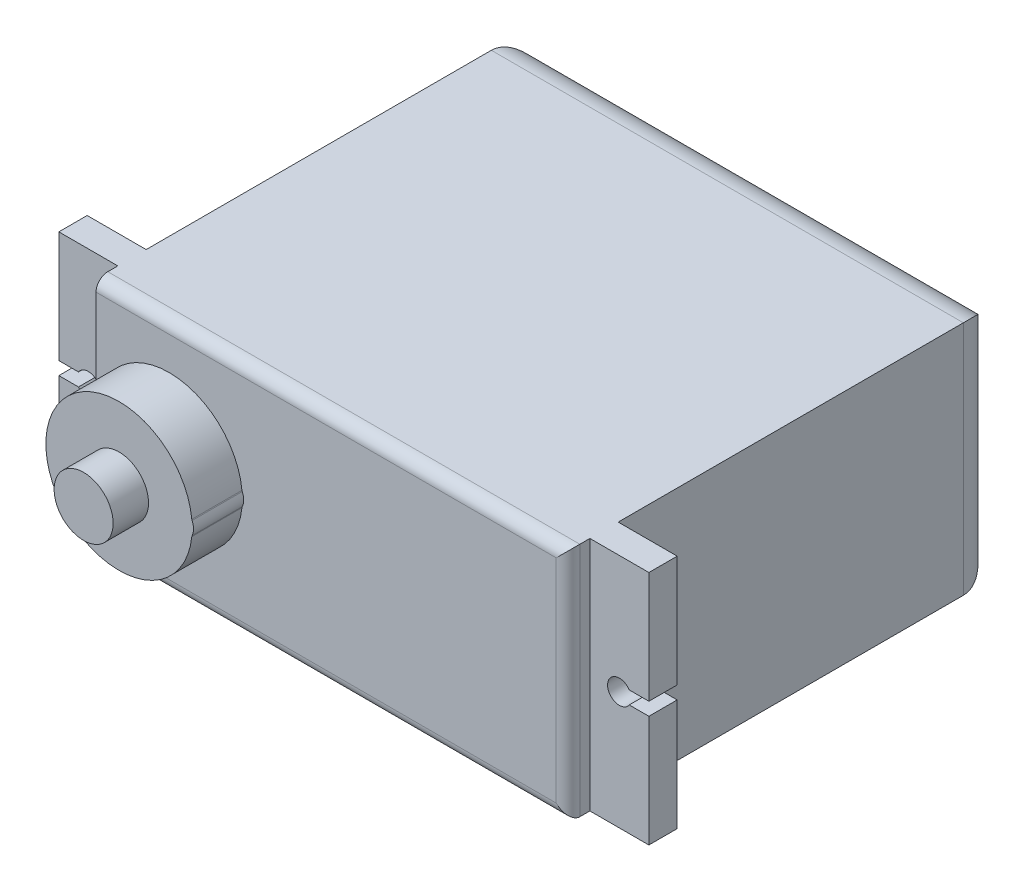
SolidWorks part; units mm, degrees
ref_plane "Front Plane" through (0, 0, 0) normal (0, 0, 1) x (1, 0, 0)
ref_plane "Top Plane" through (0, 0, 0) normal (0, 1, 0) x (1, 0, 0)
ref_plane "Right Plane" through (0, 0, 0) normal (1, 0, 0) x (0, 0, -1)
sketch "Sketch1" plane through (0, 0, 0) normal (0, 0, 1) x (1, 0, 0)
  line L1 (-20, -10) -> (20, -10)
  line L2 (-20, -10) -> (-20, 10)
  line L3 (-20, 10) -> (20, 10)
  line L4 (20, -10) -> (20, 10)
  line L5 (-20, -10) -> (20, 10) construction
  line L6 (-20, 10) -> (20, -10) construction
  point P0 (0, 0)
  dimension "D1" = 40
  dimension "D2" = 20
extrude "Boss-Extrude1" add sketch "Sketch1" along normal blind 36.5
sketch "Sketch2" plane through (0, -10, 0) normal (0, -1, 0) x (1, 0, 0)
  line L0 (20, 36.5) -> (20, 0) construction
  line L1 (20, 32.25) -> (25, 32.25)
  line L2 (20, 32.25) -> (20, 34.65)
  line L3 (20, 34.65) -> (25, 34.65)
  line L4 (25, 32.25) -> (25, 34.65)
  line L5 (-20, 36.5) -> (20, 36.5) construction
  line L6 (0, 36.5) -> (0, 0) construction
  line L7 (-20, 32.25) -> (-25, 32.25)
  line L8 (-25, 32.25) -> (-25, 34.65)
  line L9 (-20, 34.65) -> (-25, 34.65)
  line L10 (-20, 32.25) -> (-20, 34.65)
  dimension "D1" = 4.25
  dimension "D2" = 2.4
  dimension "D3" = 5
extrude "Boss-Extrude2" add sketch "Sketch2" against normal up to surface (20 mm away) up to face at (0, 10, 18.25)
sketch "Sketch3" plane through (0, 0, 34.65) normal (0, 0, 1) x (1, 0, 0)
  line L0 (-25, 0) -> (25, 0) construction
  line L1 (-25, 10) -> (-25, -10) construction
  line L2 (25, 10) -> (25, -10) construction
  line L3 (0, 10) -> (0, -10) construction
  line L4 (20, 10) -> (-20, 10) construction
  line L5 (-20, -10) -> (20, -10) construction
  line L6 (25, -0.55) -> (23.3352, -0.55)
  line L7 (-25, 0.55) -> (-23.3352, 0.55)
  line L8 (-25, 0.55) -> (-25, -0.55)
  line L9 (-25, -0.55) -> (-23.3352, -0.55)
  line L11 (25, 0.55) -> (23.3352, 0.55)
  line L12 (25, 0.55) -> (25, -0.55)
  arc A0 (-23.3352, -0.55) -> (-23.3352, 0.55) centre (-22.5, 0) ccw
  arc A1 (23.3352, -0.55) -> (23.3352, 0.55) centre (22.5, 0) cw
  dimension "D2" = 2
  dimension "D1" = 2.5
  dimension "D3" = 1.1
extrude "Cut-Extrude1" cut sketch "Sketch3" against normal through all
sketch "Sketch4" plane through (0, 0, 36.5) normal (0, 0, 1) x (1, 0, 0)
  line L0 (-20, 0) -> (20, 0) construction
  line L1 (-20, 10) -> (-20, -10) construction
  line L2 (20, -10) -> (20, 10) construction
  line L3 (-20, 10) -> (-20, -10) construction
  arc A0 (-7.633, 0.6384) -> (-7.633, -0.6384) centre (-13.8, 0) ccw
  arc A1 (-7.6102, -0.557) -> (-7.6102, 0.557) centre (-8.7848, 0) ccw
  arc A2 (-7.6102, -0.557) -> (-7.633, -0.6384) centre (-7.3843, -0.6642) ccw
  arc A3 (-7.6102, 0.557) -> (-7.633, 0.6384) centre (-7.3843, 0.6642) cw
  dimension "D1" = 12.4
  dimension "D2" = 2.6
  dimension "D3" = 0.25
extrude "Boss-Extrude3" add sketch "Sketch4" along normal blind 4.25
sketch "Sketch9" plane through (0, 0, 40.75) normal (0, 0, 1) x (1, 0, 0)
  circle A0 centre (-13.8, 0) radius 2.5
  dimension "D1" = 5
extrude "Boss-Extrude4" add sketch "Sketch9" along normal blind 3
fillet "Fillet1" radius 3 4 edges at (20, 0, 0) (0, 10, 0) (-20, 0, 0) (0, -10, 0)
fillet "Fillet2" radius 1 3 edges at (0, -10, 36.5) (20, 0, 36.5) (0, 10, 36.5)
